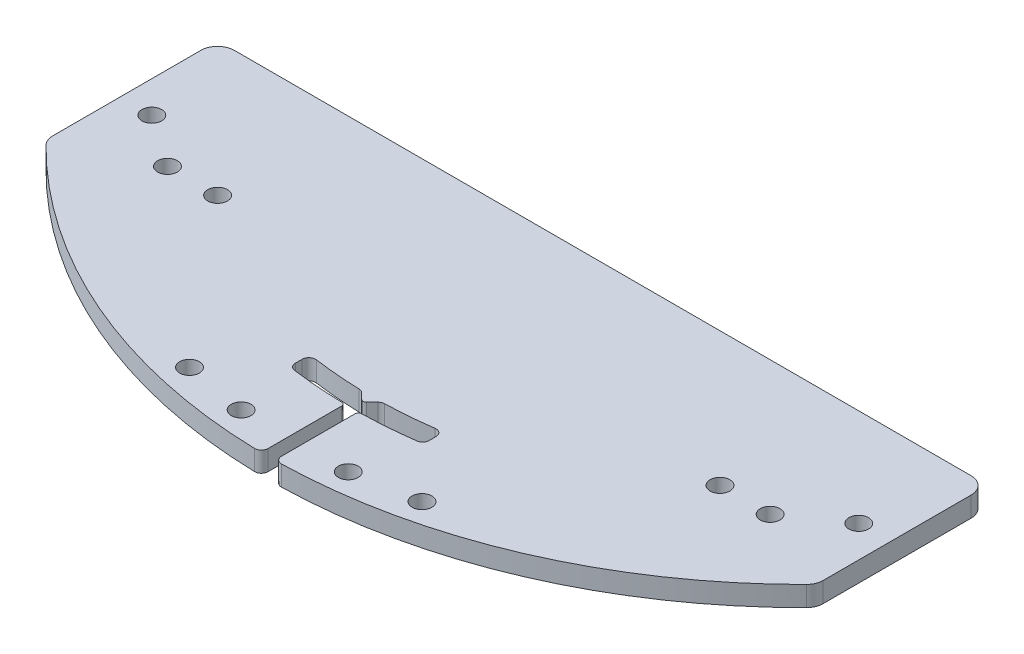
SolidWorks part; units mm, degrees
ref_plane "Front Plane" through (0, 0, 0) normal (0, 0, 1) x (1, 0, 0)
ref_plane "Top Plane" through (0, 0, 0) normal (0, 1, 0) x (1, 0, 0)
ref_plane "Right Plane" through (0, 0, 0) normal (1, 0, 0) x (0, 0, -1)
sketch "Sketch1" plane through (0, 0, 0) normal (0, 1, 0) x (1, 0, 0)
  line L0 (37.51, 0) -> (-37.51, 0) construction
  line L2 (-42.51, -5) -> (-32.51, -5)
  line L3 (-42.51, -5) -> (-42.51, 5)
  line L4 (-42.51, 5) -> (-32.51, 5)
  line L5 (-32.51, -5) -> (-32.51, 5)
  line L6 (-42.51, -5) -> (-32.51, 5) construction
  line L7 (-42.51, 5) -> (-32.51, -5) construction
  line L8 (42.51, -5) -> (32.51, -5)
  line L9 (42.51, -5) -> (42.51, 5)
  line L10 (42.51, 5) -> (32.51, 5)
  line L11 (32.51, -5) -> (32.51, 5)
  line L12 (42.51, -5) -> (32.51, 5) construction
  line L13 (42.51, 5) -> (32.51, -5) construction
  point P4 (0, 0)
  dimension "D1" = 75.02
  dimension "D2" = 10
extrude "Boss-Extrude1" add sketch "Sketch1" along normal blind 2.5
sketch "Sketch2" plane through (0, 2.5, 0) normal (0, 1, 0) x (1, 0, 0)
  line L0 (-57.51, -5.6111) -> (-57.51, 20)
  line L1 (-57.51, 20) -> (57.51, 20)
  line L2 (57.51, 20) -> (57.51, -5.6111)
  line L4 (-57.51, 7.1944) -> (-42.51, 7.1944) construction
  line L5 (-42.51, 5) -> (-42.51, -5) construction
  line L6 (57.51, 7.1944) -> (42.51, 7.1944) construction
  line L7 (42.51, -5) -> (42.51, 5) construction
  line L8 (-37.51, 5) -> (-37.51, 20) construction
  line L9 (-32.51, 5) -> (-42.51, 5) construction
  arc A0 (-57.51, -5.6111) -> (57.51, -5.6111) centre (0, 50) ccw
  dimension "D1" = 80
  dimension "D2" = 50
  dimension "D3" = 15
extrude "Boss-Extrude2" add sketch "Sketch2" along normal blind 3
sketch "Sketch3" plane through (0, 5.5, 0) normal (0, 1, 0) x (1, 0, 0)
  line L0 (-17.3557, -24.3503) -> (-8, -26) construction
  line L1 (-52.7819, 5.449) -> (-45, 0) construction
  line L2 (0, -30) -> (0, 20) construction
  line L3 (57.51, 20) -> (-57.51, 20) construction
  arc A0 (-57.51, -5.6111) -> (57.51, -5.6111) centre (0, 50) ccw construction
  point P12 (-17.3557, -24.3503)
  point P13 (-8, -26)
  point P14 (-52.7819, 5.449)
  point P15 (-45, 0)
  point P16 (45, 0)
  point P17 (52.7819, 5.449)
  point P18 (8, -26)
  point P19 (17.3557, -24.3503)
  dimension "D1" = 9.5
  dimension "D2" = 55
  dimension "D3" = 45
  dimension "D4" = 80
  dimension "D5" = 30
  dimension "D6" = 4
  dimension "D7" = 8
hole_wizard "#2 Clearance Hole1" positions "Sketch3" profile "Sketch4" hole size "#2" standard "ANSI Inch" end condition through all
sketch "Sketch4" plane through (17.3557, 5.5, 24.3503) normal (1, 0, 0) x (0, 0, 1)
  line L0 (0, 0) -> (0, 5.5)
  line L1 (0, 5.5) -> (1.4732, 5.5)
  line L2 (1.4732, 5.5) -> (1.4732, 0)
  line L5 (1.4732, 0) -> (0, 0)
  line L11 (0, -6.35) -> (0, 107.95) construction
  dimension "Thru Hole Dia." = 2.9464
  dimension "Thru Hole Depth" = 5.5
fillet "Fillet1" radius 2.5 12 edges at (-32.51, 1.25, -5) (-32.51, 1.25, 5) (-42.51, 1.25, -5) (-57.51, 4, -20) (-57.51, 4, 5.6111) (57.51, 4, 5.6111) (57.51, 4, -20) (42.51, 1.25, 5) (32.51, 1.25, 5) (-42.51, 1.25, 5) (32.51, 1.25, -5) (42.51, 1.25, -5)
sketch "Sketch5" plane through (0, 5.5, 0) normal (0, 1, 0) x (1, 0, 0)
  line L0 (-42.51, 5) -> (-32.51, -5) construction
  point P0 (-37.51, 0)
  point P1 (37.51, 0)
hole_wizard "#2 Clearance Hole2" positions "Sketch5" profile "Sketch6" hole size "#2" standard "ANSI Inch" end condition through all
sketch "Sketch6" plane through (-37.51, 5.5, 0) normal (1, 0, 0) x (0, 0, 1)
  line L0 (0, 0) -> (0, 5.5)
  line L1 (0, 5.5) -> (1.4732, 5.5)
  line L2 (1.4732, 5.5) -> (1.4732, 0)
  line L5 (1.4732, 0) -> (0, 0)
  line L11 (0, -6.35) -> (0, 107.95) construction
  dimension "Thru Hole Dia." = 2.9464
  dimension "Thru Hole Depth" = 5.5
sketch "Sketch7" plane through (0, 5.5, 0) normal (0, 1, 0) x (1, 0, 0)
  line L0 (-1, -29.9937) -> (-1, -17.5)
  line L6 (1, -17.5) -> (1, -29.9937)
  line L7 (1, -29.9937) -> (0, -30)
  line L8 (0, -30) -> (-1, -29.9937)
  line L11 (-10, -13.7276) -> (-10, -16.7626)
  line L12 (10, -13.7276) -> (10, -16.7626)
  line L13 (-1.5, -14.49) -> (0, -15.99)
  line L14 (0, -15.99) -> (1.5, -14.49)
  arc A0 (-56.7845, -6.3517) -> (56.7845, -6.3517) centre (0, 50) ccw construction
  arc A1 (-1, -17.5) -> (-10, -16.7626) centre (0, 50) cw
  arc A2 (1, -17.5) -> (10, -16.7626) centre (0, 50) ccw
  arc A3 (-10, -13.7276) -> (10, -13.7276) centre (0, 50) ccw
  point P15 (0, -14.5074)
  dimension "D2" = 3
  dimension "D1" = 2
  dimension "D3" = 20
  dimension "D4" = 12.5
  dimension "D5" = 3
extrude "Cut-Extrude1" cut sketch "Sketch7" against normal through all contours A3 L14 L13 L11 A1 L0 L8 L7 L6 A2 L12
fillet "Fillet2" radius 1 8 edges at (10, 4, 13.7276) (10, 4, 16.7626) (-10, 4, 16.7626) (-1.5, 4, 14.49) (1.5, 4, 14.49) (-10, 4, 13.7276)
fillet "Fillet3" radius 0.5 3 edges at (1, 4, 17.5) (-1, 4, 17.5) (0, 4, 15.99)
